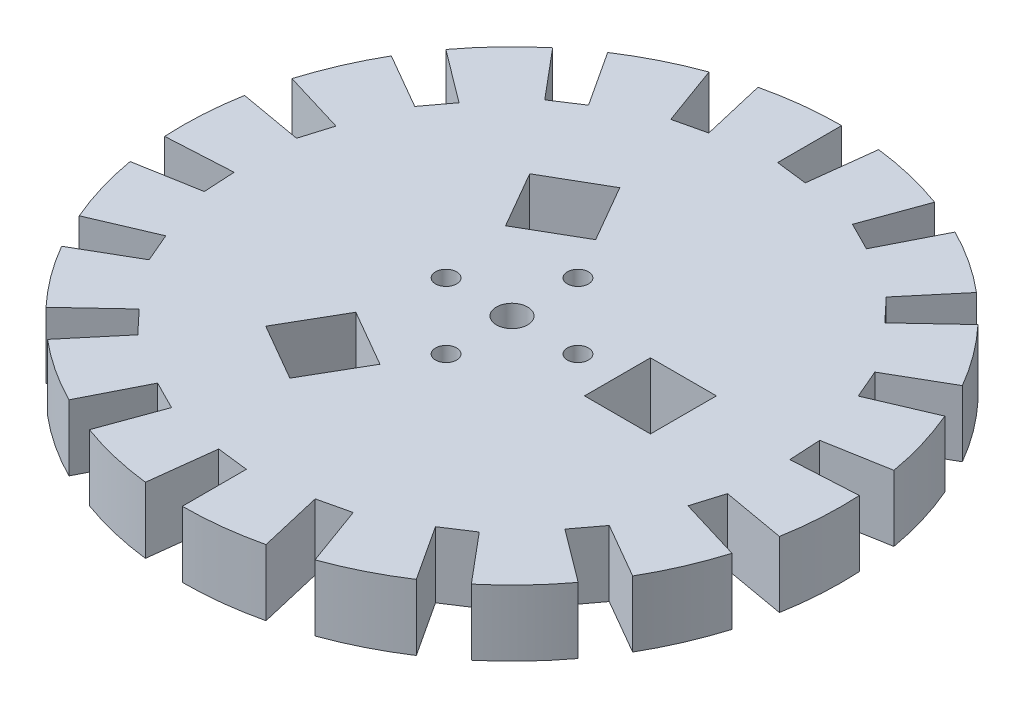
SolidWorks part; units mm, degrees
ref_plane "Front Plane" through (0, 0, 0) normal (0, 0, 1) x (1, 0, 0)
ref_plane "Top Plane" through (0, 0, 0) normal (0, 1, 0) x (1, 0, 0)
ref_plane "Right Plane" through (0, 0, 0) normal (1, 0, 0) x (0, 0, -1)
sketch "Sketch1" plane through (0, 0, 0) normal (0, 1, 0) x (1, 0, 0)
  circle A0 centre (0, 0) radius 31.75
  dimension "D1" = 63.5
extrude "Boss-Extrude1" add sketch "Sketch1" along normal blind 6.35
sketch "Sketch2" plane through (0, 6.35, 0) normal (0, 1, 0) x (1, 0, 0)
  line L0 (0, 31.75) -> (0, -31.75) construction
  line L1 (-31.75, 0) -> (31.75, 0) construction
  line L2 (3.7829, 31.5238) -> (3.0263, 25.2191)
  line L3 (3.0263, 25.2191) -> (0, 25.5822)
  line L4 (3.0263, 25.2191) -> (0, 0) construction
  line L5 (0, 25.5822) -> (0, 31.75)
  line L6 (0, 31.75) -> (0, 34.3082)
  line L7 (0, 34.3082) -> (4.0877, 34.0638)
  line L8 (4.0877, 34.0638) -> (3.7829, 31.5238)
  line L9 (14.3365, 28.3289) -> (11.4692, 22.6631)
  line L10 (11.4692, 22.6631) -> (8.7496, 24.0394)
  line L11 (8.7496, 24.0394) -> (10.8591, 29.8352)
  line L12 (10.8591, 29.8352) -> (11.7341, 32.2392)
  line L13 (11.7341, 32.2392) -> (15.4917, 30.6115)
  line L14 (15.4917, 30.6115) -> (14.3365, 28.3289)
  line L15 (23.161, 21.7171) -> (18.5288, 17.3737)
  line L16 (18.5288, 17.3737) -> (16.4439, 19.5971)
  line L17 (16.4439, 19.5971) -> (20.4085, 24.3219)
  line L18 (20.4085, 24.3219) -> (22.0529, 26.2816)
  line L19 (22.0529, 26.2816) -> (25.0271, 23.4669)
  line L20 (25.0271, 23.4669) -> (23.161, 21.7171)
  line L21 (29.1919, 12.4859) -> (23.3535, 9.9887)
  line L22 (23.3535, 9.9887) -> (22.1549, 12.7911)
  line L23 (22.1549, 12.7911) -> (27.4963, 15.875)
  line L24 (27.4963, 15.875) -> (29.7118, 17.1541)
  line L25 (29.7118, 17.1541) -> (31.544, 13.4919)
  line L26 (31.544, 13.4919) -> (29.1919, 12.4859)
  line L27 (31.7018, 1.7487) -> (25.3614, 1.3989)
  line L28 (25.3614, 1.3989) -> (25.1936, 4.4423)
  line L29 (25.1936, 4.4423) -> (31.2676, 5.5133)
  line L30 (31.2676, 5.5133) -> (33.787, 5.9576)
  line L31 (33.787, 5.9576) -> (34.2561, 1.8896)
  line L32 (34.2561, 1.8896) -> (31.7018, 1.7487)
  line L33 (30.388, -9.1994) -> (24.3104, -7.3596)
  line L34 (24.3104, -7.3596) -> (25.1936, -4.4423)
  line L35 (25.1936, -4.4423) -> (31.2676, -5.5133)
  line L36 (31.2676, -5.5133) -> (33.787, -5.9576)
  line L37 (33.787, -5.9576) -> (32.8365, -9.9407)
  line L38 (32.8365, -9.9407) -> (30.388, -9.1994)
  line L39 (25.409, -19.038) -> (20.3272, -15.2304)
  line L40 (20.3272, -15.2304) -> (22.1549, -12.7911)
  line L41 (22.1549, -12.7911) -> (27.4963, -15.875)
  line L42 (27.4963, -15.875) -> (29.7118, -17.1541)
  line L43 (29.7118, -17.1541) -> (27.4563, -20.5719)
  line L44 (27.4563, -20.5719) -> (25.409, -19.038)
  line L45 (17.3653, -26.5802) -> (13.8922, -21.2642)
  line L46 (13.8922, -21.2642) -> (16.4439, -19.5971)
  line L47 (16.4439, -19.5971) -> (20.4085, -24.3219)
  line L48 (20.4085, -24.3219) -> (22.0529, -26.2816)
  line L49 (22.0529, -26.2816) -> (18.7645, -28.7219)
  line L50 (18.7645, -28.7219) -> (17.3653, -26.5802)
  line L51 (7.2271, -30.9165) -> (5.7816, -24.7332)
  line L52 (5.7816, -24.7332) -> (8.7496, -24.0394)
  line L53 (8.7496, -24.0394) -> (10.8591, -29.8352)
  line L54 (10.8591, -29.8352) -> (11.7341, -32.2392)
  line L55 (11.7341, -32.2392) -> (7.8094, -33.4076)
  line L56 (7.8094, -33.4076) -> (7.2271, -30.9165)
  line L57 (-3.7829, -31.5238) -> (-3.0263, -25.2191)
  line L58 (-3.0263, -25.2191) -> (0, -25.5822)
  line L59 (0, -25.5822) -> (0, -31.75)
  line L60 (0, -31.75) -> (0, -34.3082)
  line L61 (0, -34.3082) -> (-4.0877, -34.0638)
  line L62 (-4.0877, -34.0638) -> (-3.7829, -31.5238)
  line L63 (-14.3365, -28.3289) -> (-11.4692, -22.6631)
  line L64 (-11.4692, -22.6631) -> (-8.7496, -24.0394)
  line L65 (-8.7496, -24.0394) -> (-10.8591, -29.8352)
  line L66 (-10.8591, -29.8352) -> (-11.7341, -32.2392)
  line L67 (-11.7341, -32.2392) -> (-15.4917, -30.6115)
  line L68 (-15.4917, -30.6115) -> (-14.3365, -28.3289)
  line L69 (-23.161, -21.7171) -> (-18.5288, -17.3737)
  line L70 (-18.5288, -17.3737) -> (-16.4439, -19.5971)
  line L71 (-16.4439, -19.5971) -> (-20.4085, -24.3219)
  line L72 (-20.4085, -24.3219) -> (-22.0529, -26.2816)
  line L73 (-22.0529, -26.2816) -> (-25.0271, -23.4669)
  line L74 (-25.0271, -23.4669) -> (-23.161, -21.7171)
  line L75 (-29.1919, -12.4859) -> (-23.3535, -9.9887)
  line L76 (-23.3535, -9.9887) -> (-22.1549, -12.7911)
  line L77 (-22.1549, -12.7911) -> (-27.4963, -15.875)
  line L78 (-27.4963, -15.875) -> (-29.7118, -17.1541)
  line L79 (-29.7118, -17.1541) -> (-31.544, -13.4919)
  line L80 (-31.544, -13.4919) -> (-29.1919, -12.4859)
  line L81 (-31.7018, -1.7487) -> (-25.3614, -1.3989)
  line L82 (-25.3614, -1.3989) -> (-25.1936, -4.4423)
  line L83 (-25.1936, -4.4423) -> (-31.2676, -5.5133)
  line L84 (-31.2676, -5.5133) -> (-33.787, -5.9576)
  line L85 (-33.787, -5.9576) -> (-34.2561, -1.8896)
  line L86 (-34.2561, -1.8896) -> (-31.7018, -1.7487)
  line L87 (-30.388, 9.1994) -> (-24.3104, 7.3596)
  line L88 (-24.3104, 7.3596) -> (-25.1936, 4.4423)
  line L89 (-25.1936, 4.4423) -> (-31.2676, 5.5133)
  line L90 (-31.2676, 5.5133) -> (-33.787, 5.9576)
  line L91 (-33.787, 5.9576) -> (-32.8365, 9.9407)
  line L92 (-32.8365, 9.9407) -> (-30.388, 9.1994)
  line L93 (-25.409, 19.038) -> (-20.3272, 15.2304)
  line L94 (-20.3272, 15.2304) -> (-22.1549, 12.7911)
  line L95 (-22.1549, 12.7911) -> (-27.4963, 15.875)
  line L96 (-27.4963, 15.875) -> (-29.7118, 17.1541)
  line L97 (-29.7118, 17.1541) -> (-27.4563, 20.5719)
  line L98 (-27.4563, 20.5719) -> (-25.409, 19.038)
  line L99 (-17.3653, 26.5802) -> (-13.8922, 21.2642)
  line L100 (-13.8922, 21.2642) -> (-16.4439, 19.5971)
  line L101 (-16.4439, 19.5971) -> (-20.4085, 24.3219)
  line L102 (-20.4085, 24.3219) -> (-22.0529, 26.2816)
  line L103 (-22.0529, 26.2816) -> (-18.7645, 28.7219)
  line L104 (-18.7645, 28.7219) -> (-17.3653, 26.5802)
  line L105 (-7.2271, 30.9165) -> (-5.7816, 24.7332)
  line L106 (-5.7816, 24.7332) -> (-8.7496, 24.0394)
  line L107 (-8.7496, 24.0394) -> (-10.8591, 29.8352)
  line L108 (-10.8591, 29.8352) -> (-11.7341, 32.2392)
  line L109 (-11.7341, 32.2392) -> (-7.8094, 33.4076)
  line L110 (-7.8094, 33.4076) -> (-7.2271, 30.9165)
  circle A0 centre (0, 0) radius 31.75 construction
  point P119 (0, 0)
  dimension "D1" = 6.35
  dimension "D2" = 3.048
  dimension "D3" = 2.54
  dimension "D4" = 18
extrude "Cut-Extrude1" cut sketch "Sketch2" against normal blind 6.35
sketch "Sketch3" plane through (0, 6.35, 0) normal (0, 1, 0) x (1, 0, 0)
  line L0 (-31.75, 0) -> (31.75, 0) construction
  line L1 (-2.3304, -10.3863) -> (-5.5054, -15.8856)
  line L2 (-2.3304, -10.3863) -> (-7.8296, -7.2113)
  line L3 (-7.8296, -7.2113) -> (-11.0046, -12.7106)
  line L4 (-5.5054, -15.8856) -> (-11.0046, -12.7106)
  line L5 (-2.3304, -10.3863) -> (-11.0046, -12.7106) construction
  line L6 (-7.8296, -7.2113) -> (-5.5054, -15.8856) construction
  line L7 (-7.8296, 7.2113) -> (-11.0046, 12.7106)
  line L8 (10.16, 3.175) -> (16.51, 3.175)
  line L9 (10.16, 3.175) -> (10.16, -3.175)
  line L10 (10.16, -3.175) -> (16.51, -3.175)
  line L11 (16.51, 3.175) -> (16.51, -3.175)
  line L12 (10.16, 3.175) -> (16.51, -3.175) construction
  line L13 (10.16, -3.175) -> (16.51, 3.175) construction
  line L14 (-7.8296, 7.2113) -> (-2.3304, 10.3863)
  line L15 (-2.3304, 10.3863) -> (-5.5054, 15.8856)
  line L16 (-11.0046, 12.7106) -> (-5.5054, 15.8856)
  line L17 (-7.8296, 7.2113) -> (-5.5054, 15.8856) construction
  line L18 (-2.3304, 10.3863) -> (-11.0046, 12.7106) construction
  circle A0 centre (0, 0) radius 1.5
  arc A1 (-31.2676, 5.5133) -> (-31.7018, -1.7487) centre (0, 0) ccw construction
  arc A2 (31.2676, -5.5133) -> (31.7018, 1.7487) centre (0, 0) ccw construction
  point P12 (7.0301, 0)
  point P16 (-6.6675, -11.5484)
  point P17 (13.335, 0)
  point P27 (-6.6675, 11.5484)
  point P32 (0, 0)
  dimension "D1" = 6.35
  dimension "D3" = 3
  dimension "D2" = 10.16
  dimension "D4" = 3
sketch "Sketch4" plane through (0, 6.35, 0) normal (0, 1, 0) x (1, 0, 0)
  circle A0 centre (0, 0) radius 6.35 construction
  circle A1 centre (6.35, 0) radius 1.016
  circle A2 centre (0, -6.35) radius 1.016
  circle A3 centre (-6.35, 0) radius 1.016
  circle A4 centre (0, 6.35) radius 1.016
  point P14 (0, 0)
  dimension "D1" = 12.7
  dimension "D2" = 2.032
  dimension "D3" = 4
extrude "Cut-Extrude2" cut sketch "Sketch3" against normal blind 6.35
extrude "Cut-Extrude3" cut sketch "Sketch4" against normal blind 6.35
equation "\"Ball Diameter\"= 1.75in"
equation "\"Ball Radius\" = \"Ball Diameter\"/2"
equation "\"Sheet Thickness\"= 0.25in"
equation "\"Screw Diameter\"= .17in"
equation "\"Robot Diameter\"= 14in"
equation "\"Castor Screw Diameter\"= 0.22in"
equation "\"Wheel Diameter\" = 4in"
equation "\"Nut Diameter\" = 8.4mm"
equation "\"Nut Height\" = 2.9mm"
equation "\"Screw Height\" = 0.55in"
equation "\"Pulley Diameter\" = 1in"
equation "\"Reactor Height\" = 14in"
equation "\"Elevator Height\" = 11.5in"
equation "\"Elevator Width\" = \"Ball Diameter\" + 0.25in"
equation "\"Elevator Bearing Diameter\" = sqr(2*(\"Sheet Thickness\"^2)) + 0.2in"
equation "\"Elevator Axle Endcap Diameter\" = \"Pulley Diameter\" + 0.25in"
equation "\"Elevator Axle Length\" = \"Elevator Width\" + 8*\"Sheet Thickness\""
equation "\"Elevator Clearance from Axis\" = 3.5in"
equation "\"Elevator Horizontal Clearance\" = \"Elevator Width\" + 0.5in"
equation "\"Claw Horizontal Seperation\" = (\"Elevator Width\"/2) - (1.5 * \"Sheet Thickness\") - 0.15in"
equation "\"Claw Radius\" = \"Ball Radius\" + 0.1in"
equation "\"Castor Wheel Height\" = 1.25in"
equation "\"Length of Chute\" = 8in"
